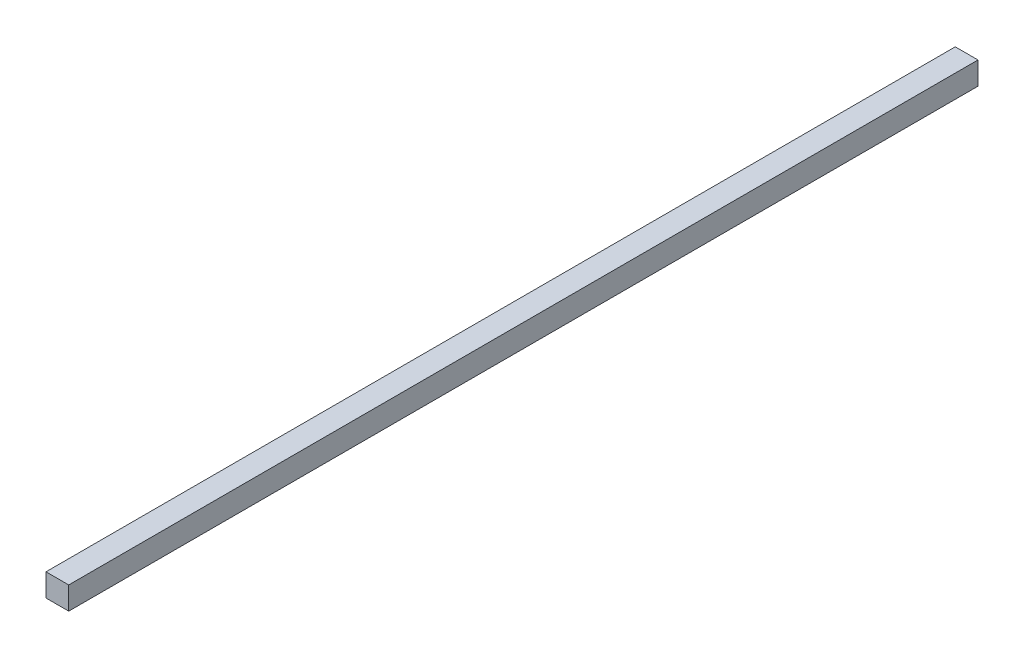
SolidWorks part; units mm, degrees
ref_plane "Front Plane" through (0, 0, 0) normal (0, 0, 1) x (1, 0, 0)
ref_plane "Top Plane" through (0, 0, 0) normal (0, 1, 0) x (1, 0, 0)
ref_plane "Right Plane" through (0, 0, 0) normal (1, 0, 0) x (0, 0, -1)
other "Configuration Table"
sketch "Sketch1" plane through (0, 0, 0) normal (0, 0, 1) x (1, 0, 0)
  line L1 (0, 0) -> (50.8, 0)
  line L2 (0, 0) -> (0, 50.8)
  line L3 (0, 50.8) -> (50.8, 50.8)
  line L4 (50.8, 0) -> (50.8, 50.8)
extrude "Extrude1" add sketch "Sketch1" along normal blind 2032
